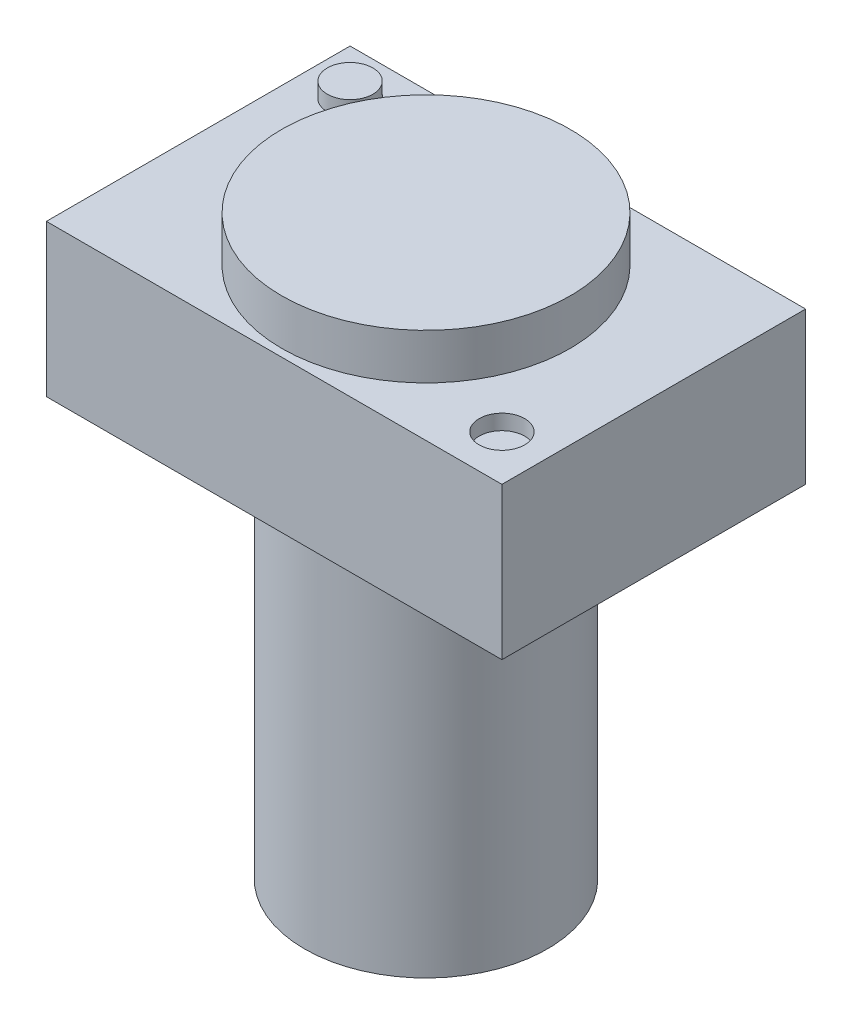
SolidWorks part; units mm, degrees
material "Unilate"
ref_plane "Front" through (0, 0, 0) normal (0, 0, 1) x (1, 0, 0)
ref_plane "Top" through (0, 0, 0) normal (0, 1, 0) x (1, 0, 0)
ref_plane "Right" through (0, 0, 0) normal (1, 0, 0) x (0, 0, -1)
sketch "Sketch1" plane through (0, 0, 0) normal (0, 1, 0) x (1, 0, 0)
  line L1 (0, 0) -> (30, 0)
  line L2 (0, 0) -> (0, 20)
  line L3 (0, 20) -> (30, 20)
  line L4 (30, 0) -> (30, 20)
  dimension "D1" = 30
  dimension "D2" = 20
extrude "Boss-Extrude1" add sketch "Sketch1" against normal blind 10
sketch "Sketch2" plane through (0, -10, 0) normal (0, -1, 0) x (1, 0, 0)
  line L0 (0, -20) -> (0, 0) construction
  line L1 (0, 0) -> (30, 0) construction
  circle A0 centre (15, -10) radius 8
  dimension "D3" = 16
  dimension "D1" = 15
  dimension "D2" = 10
extrude "Boss-Extrude2" add sketch "Sketch2" along normal blind 25
sketch "Sketch3" plane through (0, 0, 0) normal (0, 1, 0) x (1, 0, 0)
  line L3 (0, 0) -> (30, 0) construction
  line L4 (0, 20) -> (0, 0) construction
  circle A2 centre (15, 10) radius 9.5
  dimension "D2" = 10
  dimension "D1" = 19
  dimension "D3" = 15
extrude "Boss-Extrude3" add sketch "Sketch3" along normal blind 3
sketch "Sketch4" plane through (0, 0, 0) normal (0, 1, 0) x (1, 0, 0)
  line L0 (0, 20) -> (0, 0) construction
  line L1 (30, 20) -> (0, 20) construction
  circle A0 centre (3, 17) radius 1.5
  dimension "D1" = 3
  dimension "D2" = 3
  dimension "D3" = 3
extrude "Boss-Extrude4" add sketch "Sketch4" along normal blind 1
sketch "Sketch5" plane through (0, 0, 0) normal (0, 1, 0) x (1, 0, 0)
  line L0 (30, 0) -> (30, 20) construction
  line L1 (0, 0) -> (30, 0) construction
  circle A0 centre (27, 3) radius 1.5
  dimension "D1" = 3
  dimension "D3" = 3
  dimension "D2" = 3
extrude "Cut-Extrude1" cut sketch "Sketch5" against normal blind 1
